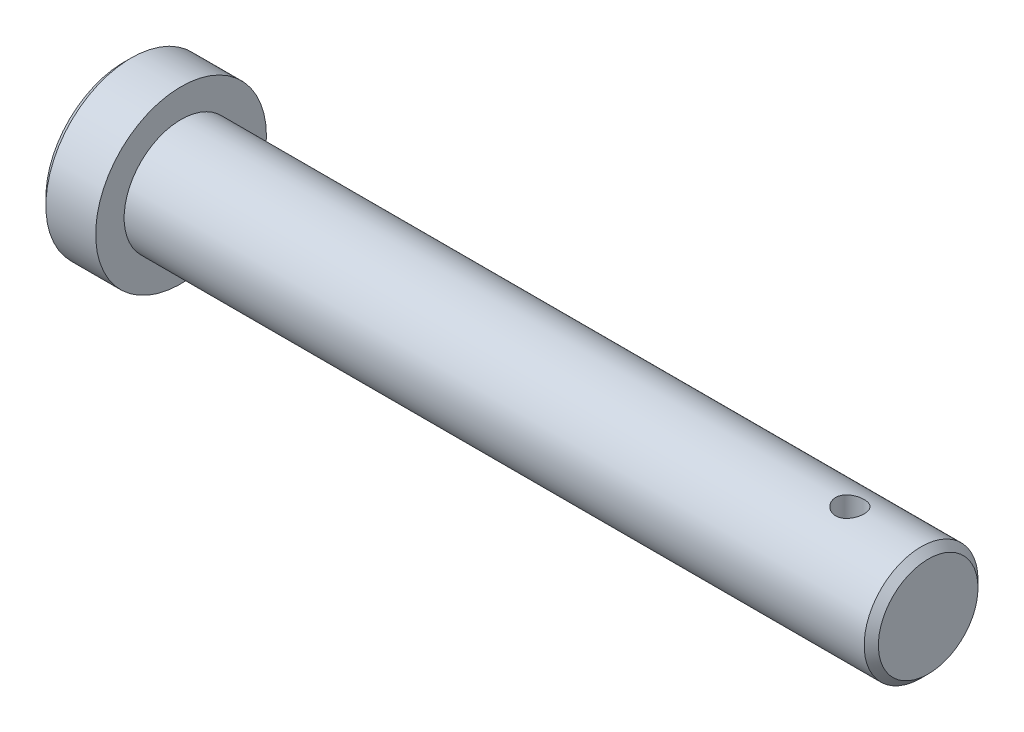
SolidWorks part; units mm, degrees
ref_plane "Front Plane" through (0, 0, 0) normal (0, 0, 1) x (1, 0, 0)
ref_plane "Top Plane" through (0, 0, 0) normal (0, 1, 0) x (1, 0, 0)
ref_plane "Right Plane" through (0, 0, 0) normal (1, 0, 0) x (0, 0, -1)
sketch "Sketch1" plane through (0, 0, 0) normal (1, 0, 0) x (0, 0, -1)
  circle A0 centre (0, 0) radius 12
extrude "Boss-Extrude1" add sketch "Sketch1" along normal blind 8
chamfer "Chamfer1" distance 1 angle 45 1 edges at (0, 0, -12)
sketch "Sketch2" plane through (8, 0, 0) normal (1, 0, 0) x (0, 0, -1)
  circle A0 centre (0, 0) radius 8
extrude "Boss-Extrude2" add sketch "Sketch2" along normal blind 105
chamfer "Chamfer2" distance 1 angle 45 1 edges at (113, 0, -8)
sketch "Sketch3" plane through (0, 0, 0) normal (0, 1, 0) x (1, 0, 0)
  line L0 (8, -8) -> (8, 8) construction
  circle A0 centre (102, 0) radius 2
  dimension "D1" = 94
extrude "Cut-Extrude1" cut sketch "Sketch3" against normal through all both and the other way through all
